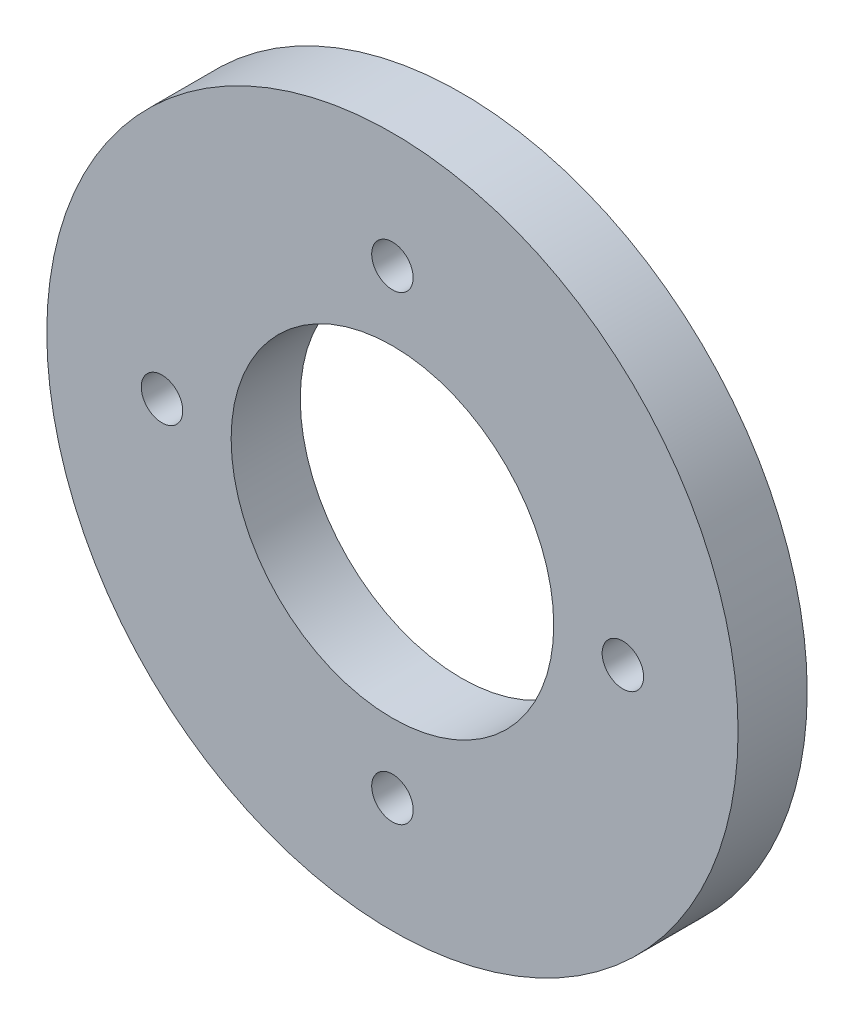
SolidWorks part; units mm, degrees
ref_plane "Front Plane" through (0, 0, 0) normal (0, 0, 1) x (1, 0, 0)
ref_plane "Top Plane" through (0, 0, 0) normal (0, 1, 0) x (1, 0, 0)
ref_plane "Right Plane" through (0, 0, 0) normal (1, 0, 0) x (0, 0, -1)
sketch "Sketch1" plane through (0, 0, 0) normal (0, 0, 1) x (1, 0, 0)
  line L0 (0, 0) -> (0, -15) construction
  circle A0 centre (0, 0) radius 15
  circle A1 centre (0, -10) radius 0.9
  circle A2 centre (-10, 0) radius 0.9
  circle A3 centre (0, 10) radius 0.9
  circle A4 centre (10, 0) radius 0.9
  point P15 (0, 0)
  dimension "D1" = 5
  dimension "D2" = 4
extrude "Boss-Extrude1" add sketch "Sketch1" along normal blind 3
sketch "Sketch2" plane through (0, 0, 0) normal (0, 0, -1) x (-1, 0, 0)
  circle A0 centre (0, 0) radius 7
extrude "Cut-Extrude1" cut sketch "Sketch2" against normal blind 5.5
